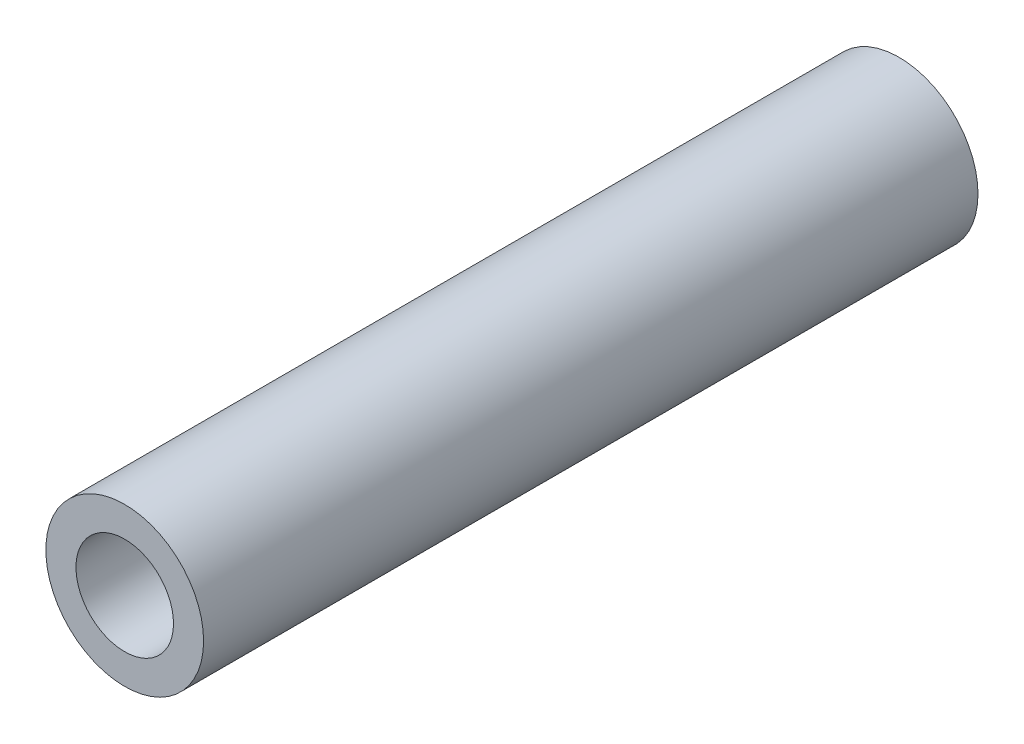
SolidWorks part; units mm, degrees
material "ABS"
ref_plane "前视基准面" through (0, 0, 0) normal (0, 0, 1) x (1, 0, 0)
ref_plane "上视基准面" through (0, 0, 0) normal (0, 1, 0) x (1, 0, 0)
ref_plane "右视基准面" through (0, 0, 0) normal (1, 0, 0) x (0, 0, -1)
sketch "草图1" plane through (0, 0, 0) normal (0, 0, 1) x (1, 0, 0)
  circle A0 centre (0, 0) radius 1.7
  circle A1 centre (0, 0) radius 2.75
  dimension "D1" = 5.5
  dimension "D2" = 3.4
extrude "凸台-拉伸1" add sketch "草图1" along normal blind 27
